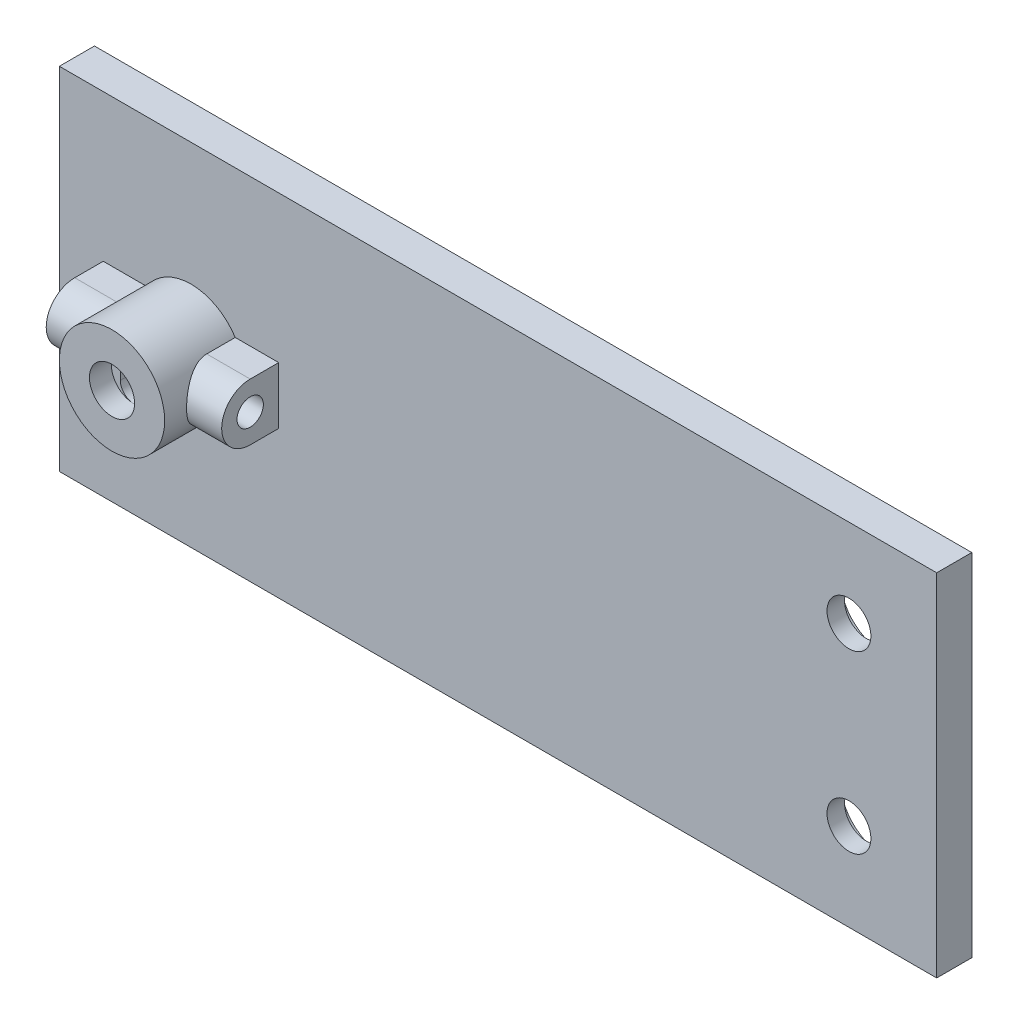
SolidWorks part; units mm, degrees
ref_plane "Front Plane" through (0, 0, 0) normal (0, 0, 1) x (1, 0, 0)
ref_plane "Top Plane" through (0, 0, 0) normal (0, 1, 0) x (1, 0, 0)
ref_plane "Right Plane" through (0, 0, 0) normal (1, 0, 0) x (0, 0, -1)
sketch "Sketch1" plane through (0, 0, 0) normal (0, 0, 1) x (1, 0, 0)
  line L1 (0, 0) -> (170, 0)
  line L2 (0, 0) -> (0, 40)
  line L3 (0, 40) -> (170, 40)
  line L4 (170, 0) -> (170, 40)
  dimension "D1" = 170
  dimension "D2" = 40
extrude "Boss-Extrude1" add sketch "Sketch1" along normal blind 4
sketch "Sketch2" plane through (0, 0, 4) normal (0, 0, 1) x (1, 0, 0)
  line L0 (85, 18.975) -> (85, 21.025) construction
  line L1 (83.45, 18.975) -> (83.45, 21.025)
  line L2 (86.55, 18.975) -> (86.55, 21.025)
  line L3 (0, 40) -> (0, 0) construction
  line L4 (170, 40) -> (0, 40) construction
  arc A0 (83.45, 18.975) -> (86.55, 18.975) centre (85, 18.975) ccw
  arc A1 (86.55, 21.025) -> (83.45, 21.025) centre (85, 21.025) ccw
  circle A2 centre (85, 20) radius 6
  point P2 (85, 20)
  point P10 (0, 20)
  point P13 (85, 40)
  dimension "D2" = 5.15
  dimension "D3" = 12
  dimension "D1" = 3.1
extrude "Boss-Extrude2" add sketch "Sketch2" along normal blind 9
sketch "Sketch3" plane through (0, 0, 13) normal (0, 0, 1) x (1, 0, 0)
  circle A0 centre (85, 20) radius 6 construction
  circle A1 centre (85, 20) radius 6 construction
  circle A2 centre (85, 20) radius 2.575
  dimension "D1" = 5.15
extrude "Cut-Extrude1" cut sketch "Sketch3" against normal blind 2.5
sketch "Sketch4" plane through (83.45, 0, 0) normal (1, 0, 0) x (0, 0, -1)
  line L0 (-4, 21.025) -> (-4, 18.975) construction
  line L1 (-10.5, 18.975) -> (-4, 18.975) construction
  circle A0 centre (-7.25, 20) radius 1.25
  point P4 (0, 0)
  point P5 (-4, 20)
  point P8 (-7.25, 18.975)
  dimension "D1" = 2.5
extrude "Cut-Extrude2" cut sketch "Sketch4" against normal up to surface and the other way up to surface up to face at (91, 20, 13) other way up to face at (91, 20, 13)
ref_plane "Plane1" through (91, 0, 0) normal (1, 0, 0) x (0, 0, -1)
sketch "Sketch6" plane through (91, 0, 0) normal (1, 0, 0) x (0, 0, -1)
  line L0 (-4, 26) -> (-4, 14) construction
  line L1 (-7.25, 23.25) -> (-4, 23.25)
  line L2 (-4, 23.25) -> (-4, 16.75)
  line L3 (-4, 16.75) -> (-7.25, 16.75)
  circle A0 centre (-7.25, 20) radius 1.25 construction
  circle A1 centre (-7.25, 20) radius 1.25 construction
  arc A3 (-7.25, 23.25) -> (-7.25, 16.75) centre (-7.25, 20) ccw
  circle A4 centre (-7.25, 20) radius 1.5
  dimension "D1" = 3
extrude "Boss-Extrude3" add sketch "Sketch6" along normal blind 4 and the other way blind 1
ref_plane "Plane2" through (85, 0, 0) normal (-1, 0, 0) x (0, 0, 1)
mirror "Mirror1" about plane through (85, 0, 0) normal (-1, 0, 0) of "Boss-Extrude3"
sketch "Sketch8" plane through (0, 0, 0) normal (0, 0, -1) x (-1, 0, 0)
  line L5 (-170, 0) -> (-170, 40) construction
  line L6 (0, 0) -> (-170, 0) construction
  line L7 (-170, 40) -> (0, 40) construction
  circle A0 centre (-160, 30) radius 5
  circle A1 centre (-160, 10) radius 5
  point P4 (0, 0)
  point P5 (0, 0)
  dimension "D1" = 10
  dimension "D2" = 10
  dimension "D3" = 10
  dimension "D4" = 10
extrude "Cut-Extrude3" cut sketch "Sketch8" against normal blind 2
sketch "Sketch9" plane through (0, 0, 2) normal (0, 0, -1) x (-1, 0, 0)
  circle A0 centre (-160, 30) radius 5 construction
  circle A1 centre (-160, 10) radius 5 construction
  circle A2 centre (-160, 30) radius 5 construction
  circle A3 centre (-160, 10) radius 5 construction
  circle A4 centre (-160, 10) radius 2.5
  circle A5 centre (-160, 30) radius 2.5
  dimension "D1" = 5
extrude "Cut-Extrude4" cut sketch "Sketch9" against normal up to next
sketch "Sketch10" plane through (0, 0, 4) normal (0, 0, 1) x (1, 0, 0)
  line L0 (170, 40) -> (0, 40) construction
  line L1 (0, 0) -> (70, 0)
  line L2 (0, 0) -> (0, 40)
  line L3 (0, 40) -> (70, 40)
  line L4 (70, 0) -> (70, 40)
  line L5 (75, 23.25) -> (75, 16.75) construction
  dimension "D1" = 5
extrude "Cut-Extrude5" cut sketch "Sketch10" against normal up to next
